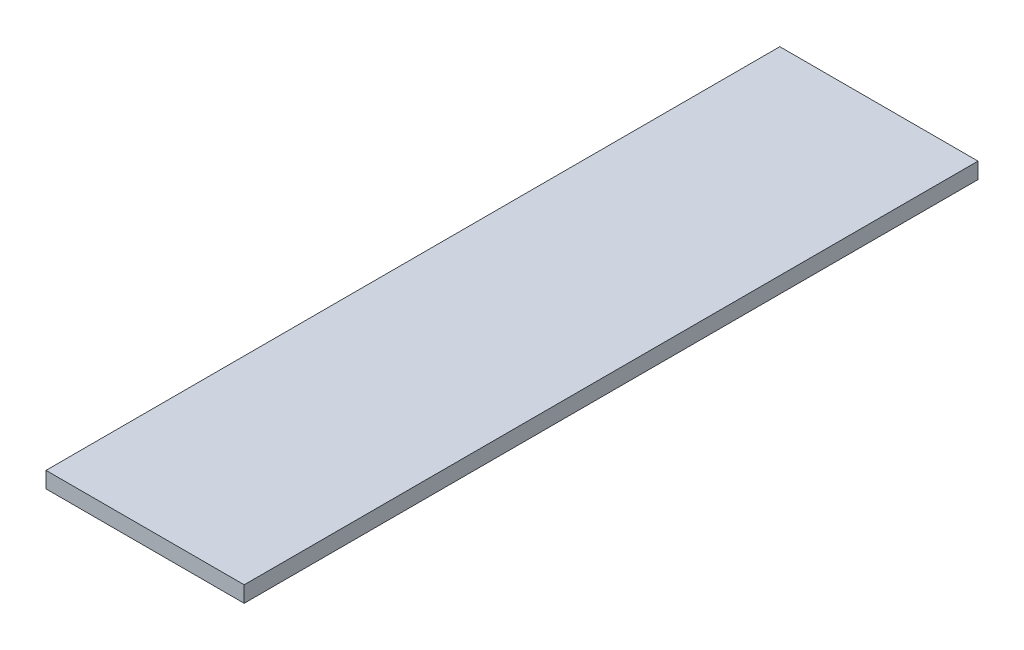
SolidWorks part; units mm, degrees
ref_plane "Front" through (0, 0, 0) normal (0, 0, 1) x (1, 0, 0)
ref_plane "Top" through (0, 0, 0) normal (0, 1, 0) x (1, 0, 0)
ref_plane "Right" through (0, 0, 0) normal (1, 0, 0) x (0, 0, -1)
sketch "Sketch1" plane through (0, 0, 0) normal (0, 1, 0) x (1, 0, 0)
  line L1 (-37, -137) -> (37, -137)
  line L2 (-37, -137) -> (-37, 137)
  line L3 (-37, 137) -> (37, 137)
  line L4 (37, -137) -> (37, 137)
  line L5 (-37, -137) -> (37, 137) construction
  line L6 (-37, 137) -> (37, -137) construction
  point P0 (0, 0)
  dimension "D1" = 274
  dimension "D2" = 74
extrude "Boss-Extrude1" add sketch "Sketch1" along normal blind 6
